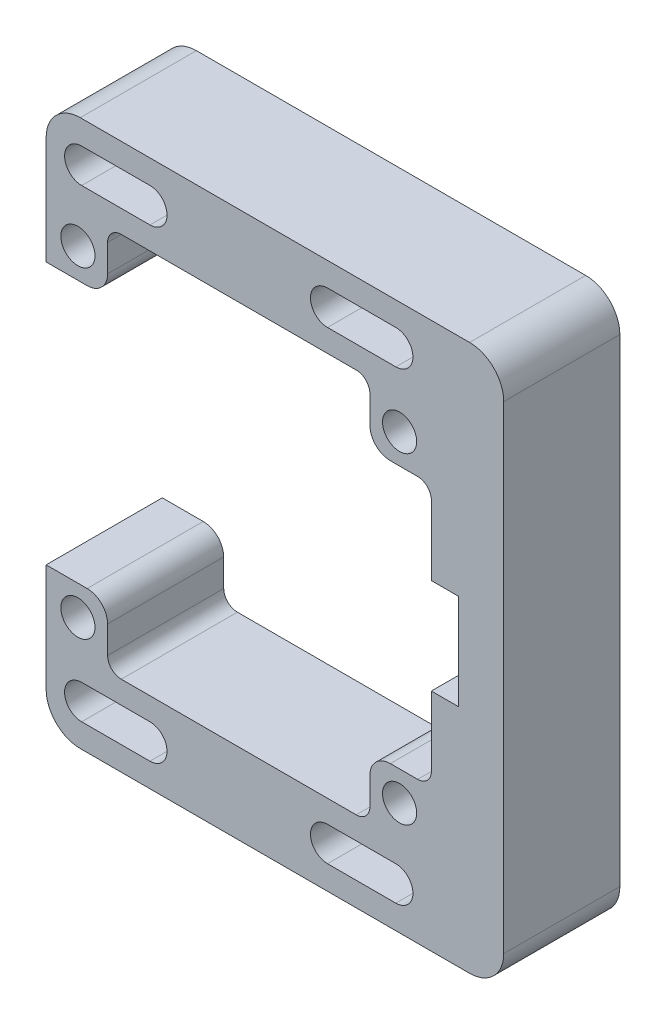
SolidWorks part; units mm, degrees
ref_plane "Alzado" through (0, 0, 0) normal (0, 0, 1) x (1, 0, 0)
ref_plane "Planta" through (0, 0, 0) normal (0, 1, 0) x (1, 0, 0)
ref_plane "Vista lateral" through (0, 0, 0) normal (1, 0, 0) x (0, 0, -1)
sketch "Croquis3" plane through (0, 0, 0) normal (0, 0, 1) x (1, 0, 0)
  line L0 (-28.2, 19.2) -> (28.2, 19.2) construction
  line L1 (-28.2, 28.2) -> (28.2, 28.2) construction
  line L2 (-28.2, 28.2) -> (-28.2, -28.2) construction
  line L3 (-28.2, -28.2) -> (28.2, -28.2) construction
  line L4 (28.2, 28.2) -> (28.2, -28.2) construction
  line L5 (-28.2, 28.2) -> (28.2, -28.2) construction
  line L6 (-28.2, -28.2) -> (28.2, 28.2) construction
  line L7 (-28.2, -19.2) -> (28.2, -19.2) construction
  line L8 (-19.2, 28.2) -> (-19.2, -28.2) construction
  line L9 (19.2, 28.2) -> (19.2, -28.2) construction
  line L11 (-23.55, 23.55) -> (23.55, 23.55) construction
  line L12 (-23.55, 23.55) -> (-23.55, -23.55) construction
  line L13 (-23.55, -23.55) -> (23.55, -23.55) construction
  line L14 (23.55, 23.55) -> (23.55, -23.55) construction
  line L15 (-23.55, 23.55) -> (23.55, -23.55) construction
  line L16 (-23.55, -23.55) -> (23.55, 23.55) construction
  circle A0 centre (-23.55, 23.55) radius 2.5
  circle A1 centre (23.55, 23.55) radius 2.5
  circle A2 centre (-23.55, -23.55) radius 2.5
  circle A3 centre (23.55, -23.55) radius 2.5
  point P0 (0, 0)
  dimension "D9" = 5
  dimension "D10" = 5
  dimension "D11" = 5
  dimension "D12" = 5
  dimension "D1" = 56.4
  dimension "D2" = 56.4
  dimension "D3" = 9
  dimension "D4" = 9
  dimension "D5" = 9
  dimension "D6" = 9
  dimension "D7" = 47.1
  dimension "D8" = 47.1
sketch "Croquis1" plane through (0, 0, 0) normal (0, 0, 1) x (1, 0, 0)
  line L1 (-28.2, -40) -> (38.8, -40)
  line L2 (-28.2, -40) -> (-28.2, 40)
  line L3 (-28.2, 40) -> (38.8, 40)
  line L4 (38.8, -40) -> (38.8, 40)
  dimension "D1" = 80
  dimension "D2" = 67
  dimension "D3" = 28.2
  dimension "D4" = 40
extrude "Saliente-Extruir1" add sketch "Croquis1" along normal blind 17
sketch "Croquis4" plane through (0, 0, 17) normal (0, 0, 1) x (1, 0, 0)
  line L0 (-28.2, 19.2) -> (-19.2, 19.2)
  line L1 (-28.2, 19.2) -> (28.2, 19.2) construction
  line L2 (-19.2, 28.2) -> (-19.2, -28.2) construction
  line L3 (-19.2, 28.2) -> (19.2, 28.2)
  line L4 (19.2, 28.2) -> (19.2, 19.2)
  line L5 (19.2, 28.2) -> (19.2, -28.2) construction
  line L6 (19.2, 19.2) -> (28.2, 19.2)
  line L7 (28.2, 19.2) -> (28.2, -19.2)
  line L8 (28.2, -19.2) -> (19.2, -19.2)
  line L9 (-28.2, 28.2) -> (28.2, -28.2) construction
  line L10 (-28.2, -19.2) -> (28.2, -19.2) construction
  line L11 (19.2, -19.2) -> (19.2, -28.2)
  line L12 (19.2, -28.2) -> (-19.2, -28.2)
  line L13 (-19.2, -28.2) -> (-19.2, -19.2)
  line L14 (-28.2, -28.2) -> (28.2, 28.2) construction
  line L15 (-19.2, -19.2) -> (-28.2, -19.2)
  line L16 (-28.2, -19.2) -> (-28.2, 19.2)
  line L17 (-19.2, 28.2) -> (-19.2, 19.2)
extrude "Cortar-Extruir2" cut sketch "Croquis4" against normal through all
sketch "Croquis5" plane through (0, 0, 17) normal (0, 0, 1) x (1, 0, 0)
  line L0 (-28.2, 34) -> (37.9229, 34) construction
  line L1 (-28.2, 40) -> (-28.2, 19.2) construction
  line L2 (-28.2, -34) -> (38.8, -34) construction
  line L3 (-28.2, -19.2) -> (-28.2, -40) construction
  line L4 (38.8, -40) -> (38.8, 40) construction
  line L6 (-18, 40) -> (-18, -40) construction
  line L7 (38.8, 40) -> (-28.2, 40) construction
  line L8 (-28.2, -40) -> (38.8, -40) construction
  line L9 (18, 40) -> (18, -40) construction
  line L10 (-23, 34) -> (-13, 34) construction
  line L11 (-23, 36.5) -> (-13, 36.5)
  line L12 (-23, 31.5) -> (-13, 31.5)
  line L13 (13, 34) -> (23, 34) construction
  line L14 (13, 36.5) -> (23, 36.5)
  line L15 (13, 31.5) -> (23, 31.5)
  line L16 (-23, -34) -> (-13, -34) construction
  line L17 (-23, -31.5) -> (-13, -31.5)
  line L18 (-23, -36.5) -> (-13, -36.5)
  line L19 (13, -34) -> (23, -34) construction
  line L20 (13, -31.5) -> (23, -31.5)
  line L21 (13, -36.5) -> (23, -36.5)
  circle A0 centre (-23.55, 23.55) radius 2.5
  circle A1 centre (23.55, 23.55) radius 2.5
  circle A2 centre (23.55, -23.55) radius 2.5
  circle A3 centre (-23.55, -23.55) radius 2.5
  arc A4 (-23, 36.5) -> (-23, 31.5) centre (-23, 34) ccw
  arc A5 (-13, 31.5) -> (-13, 36.5) centre (-13, 34) ccw
  arc A6 (13, 36.5) -> (13, 31.5) centre (13, 34) ccw
  arc A7 (23, 31.5) -> (23, 36.5) centre (23, 34) ccw
  arc A8 (-23, -31.5) -> (-23, -36.5) centre (-23, -34) ccw
  arc A9 (-13, -36.5) -> (-13, -31.5) centre (-13, -34) ccw
  arc A10 (13, -31.5) -> (13, -36.5) centre (13, -34) ccw
  arc A11 (23, -36.5) -> (23, -31.5) centre (23, -34) ccw
  point P33 (-18, 34)
  point P39 (18, 34)
  point P46 (-18, -34)
  point P53 (18, -34)
  dimension "D1" = 34
  dimension "D5" = 2.5
  dimension "D8" = 2.5
  dimension "D10" = 2.5
  dimension "D12" = 2.5
  dimension "D2" = 34
  dimension "D3" = 18
  dimension "D4" = 18
  dimension "D6" = 10
  dimension "D7" = 10
  dimension "D9" = 10
  dimension "D11" = 10
extrude "Cortar-Extruir3" cut sketch "Croquis5" against normal through all
fillet "Redondeo1" radius 2 6 edges at (-19.2, -28.2, 8.5) (19.2, -28.2, 8.5) (28.2, -19.2, 8.5) (28.2, 19.2, 8.5) (19.2, 28.2, 8.5) (-19.2, 28.2, 8.5)
fillet "Redondeo2" radius 3 4 edges at (-19.2, -19.2, 8.5) (19.2, -19.2, 8.5) (19.2, 19.2, 8.5) (-19.2, 19.2, 8.5)
fillet "Redondeo3" radius 5 4 edges at (38.8, -40, 8.5) (-28.2, -40, 8.5) (38.8, 40, 8.5) (-28.2, 40, 8.5)
sketch "Croquis6" plane through (0, 0, 17) normal (0, 0, 1) x (1, 0, 0)
  line L0 (28.2, 28.2) -> (28.2, -28.2) construction
  line L1 (24.2, 7) -> (32.2, 7)
  line L2 (24.2, 7) -> (24.2, -7)
  line L3 (24.2, -7) -> (32.2, -7)
  line L4 (32.2, 7) -> (32.2, -7)
  line L5 (24.2, 7) -> (32.2, -7) construction
  line L6 (24.2, -7) -> (32.2, 7) construction
  point P0 (28.2, 0)
  dimension "D1" = 14
  dimension "D2" = 8
extrude "Cortar-Extruir4" cut sketch "Croquis6" against normal through all
